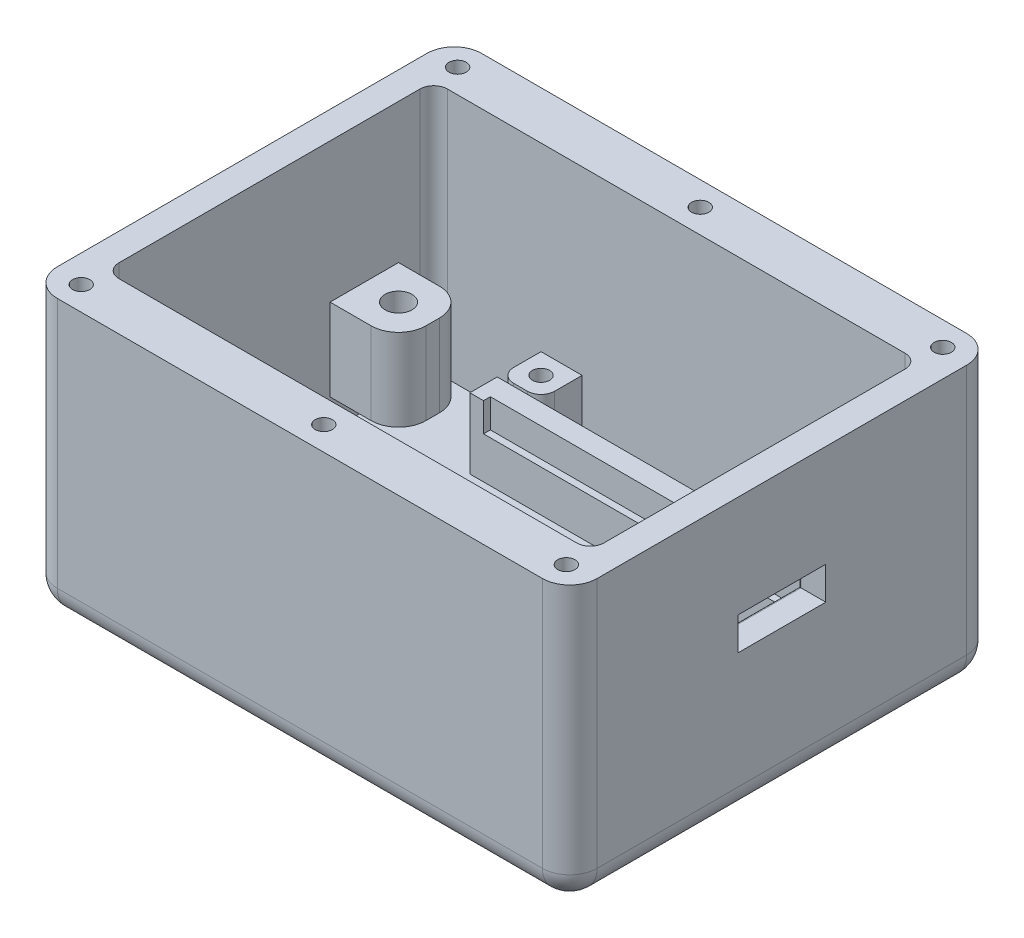
SolidWorks part; units mm, degrees
ref_plane "Front Plane" through (0, 0, 0) normal (0, 0, 1) x (1, 0, 0)
ref_plane "Top Plane" through (0, 0, 0) normal (0, 1, 0) x (1, 0, 0)
ref_plane "Right Plane" through (0, 0, 0) normal (1, 0, 0) x (0, 0, -1)
sketch "Sketch1" plane through (0, 0, 0) normal (0, 1, 0) x (1, 0, 0)
  line L1 (-38.0142, 8.7924) -> (6.9946, 8.7924)
  line L2 (-38.0142, 8.7924) -> (-38.0142, -21.6876)
  line L3 (-38.0142, -21.6876) -> (6.9946, -21.6876)
  line L4 (6.9946, 8.7924) -> (6.9946, -21.6876)
  line L5 (-40.5542, 13.2374) -> (9.5346, 13.2374)
  line L6 (-40.5542, 13.2374) -> (-40.5542, -26.1326)
  line L7 (-40.5542, -26.1326) -> (9.5346, -26.1326)
  line L8 (9.5346, 13.2374) -> (9.5346, -26.1326)
  dimension "D1" = 30.48
  dimension "D2" = 45.0088
  dimension "D3" = 4.445
  dimension "D4" = 4.445
  dimension "D5" = 2.54
  dimension "D6" = 2.54
extrude "Boss-Extrude1" add sketch "Sketch1" along normal blind 23.2918
sketch "Sketch2" plane through (0, 0, 0) normal (0, -1, 0) x (1, 0, 0)
  line L1 (-40.5542, 26.1326) -> (9.5346, 26.1326)
  line L2 (-40.5542, 26.1326) -> (-40.5542, -13.2374)
  line L3 (-40.5542, -13.2374) -> (9.5346, -13.2374)
  line L4 (9.5346, 26.1326) -> (9.5346, -13.2374)
extrude "Boss-Extrude2" add sketch "Sketch2" along normal blind 2.54
sketch "Sketch3" plane through (0, 0, 0) normal (0, 1, 0) x (1, 0, 0)
  line L1 (-28.0574, 4.7284) -> (4.4546, 4.7284)
  line L2 (-28.0574, 4.7284) -> (-28.0574, 2.1884)
  line L3 (-28.0574, 2.1884) -> (4.4546, 2.1884)
  line L4 (4.4546, 4.7284) -> (4.4546, 2.1884)
  line L5 (-28.0574, -15.0836) -> (4.4546, -15.0836)
  line L6 (-28.0574, -15.0836) -> (-28.0574, -17.6236)
  line L7 (-28.0574, -17.6236) -> (4.4546, -17.6236)
  line L8 (4.4546, -15.0836) -> (4.4546, -17.6236)
  line L10 (-38.0142, -21.6876) -> (6.9946, -21.6876) construction
  line L11 (6.9946, -21.6876) -> (6.9946, 8.7924) construction
  dimension "D1" = 2.54
  dimension "D2" = 2.54
  dimension "D3" = 17.272
  dimension "D4" = 4.064
  dimension "D5" = 32.512
  dimension "D6" = 32.512
  dimension "D7" = 2.54
  dimension "D8" = 2.54
extrude "Boss-Extrude3" add sketch "Sketch3" along normal blind 6.5278
hole_wizard "Ø1.6 (1.6) Diameter Hole1" positions "Sketch8" profile "Sketch7" hole size "Ø1.6" standard "ANSI Metric"
sketch "Sketch8" plane through (0, 23.2918, 0) normal (0, 1, 0) x (1, 0, 0)
  line L2 (-40.5542, -26.1326) -> (9.5346, -26.1326) construction
  line L3 (9.5346, 13.2374) -> (-40.5542, 13.2374) construction
  line L4 (-40.5542, 13.2374) -> (-40.5542, -26.1326) construction
  line L5 (9.5346, -26.1326) -> (9.5346, 13.2374) construction
  point P0 (-38.0142, -23.9101)
  point P2 (6.9946, -23.9101)
  point P4 (6.9946, 11.0149)
  point P6 (-38.0142, 11.0149)
  point P8 (-15.5098, 11.0149)
  point P10 (-15.5098, -23.9101)
  point P23 (-15.5098, -26.1326)
  point P24 (-15.5098, 13.2374)
  dimension "D2" = 2.54
  dimension "D3" = 2.54
  dimension "D4" = 2.54
  dimension "D5" = 2.2225
  dimension "D6" = 2.2225
  dimension "D7" = 2.2225
  dimension "D8" = 2.2225
  dimension "D9" = 0
  dimension "D10" = 0
  dimension "D11" = 2.54
  dimension "D12" = 2.2225
  dimension "D13" = 2.2225
sketch "Sketch7" plane through (-38.0142, 23.2918, 23.9101) normal (1, 0, 0) x (0, 0, 1)
  line L0 (0, 0) -> (0, 5.08)
  line L1 (0, 5.08) -> (0.8, 5.08)
  line L2 (0.8, 5.08) -> (0.8, 0)
  line L5 (0.8, 0) -> (0, 0)
  line L10 (0, 5.08) -> (-0.8, 5.08) construction
  line L11 (0, -6.35) -> (0, 107.95) construction
  dimension "Hole Dia." = 1.6
  dimension "Hole Depth" = 5.08
  dimension "Drill Angle" = 180
fillet "Fillet1" radius 2.54 8 edges at (9.5346, -2.54, 6.4476) (-15.5098, -2.54, -13.2374) (-40.5542, -2.54, 6.4476) (-15.5098, -2.54, 26.1326) (9.5346, 10.3759, 26.1326) (-40.5542, 10.3759, 26.1326) (-40.5542, 10.3759, -13.2374) (9.5346, 10.3759, -13.2374)
sketch "Sketch12" plane through (-38.0142, 0, 0) normal (1, 0, 0) x (0, 0, -1)
  line L0 (-21.6876, 23.2918) -> (-21.6876, 0) construction
  line L1 (-18.4237, 10.3378) -> (-12.0737, 10.3378)
  line L2 (-18.4237, 10.3378) -> (-18.4237, 2.7178)
  line L3 (-18.4237, 2.7178) -> (-12.0737, 2.7178)
  line L4 (-12.0737, 10.3378) -> (-12.0737, 2.7178)
  line L5 (-0.8215, 10.3378) -> (5.5285, 10.3378)
  line L6 (-0.8215, 10.3378) -> (-0.8215, 2.7178)
  line L7 (-0.8215, 2.7178) -> (5.5285, 2.7178)
  line L8 (5.5285, 10.3378) -> (5.5285, 2.7178)
  line L9 (8.7924, 0) -> (-21.6876, 0) construction
  line L10 (8.7924, 23.2918) -> (8.7924, 0) construction
  dimension "D1" = 6.35
  dimension "D2" = 6.35
  dimension "D3" = 7.62
  dimension "D4" = 7.62
  dimension "D5" = 3.2639
  dimension "D6" = 3.2639
  dimension "D7" = 2.7178
  dimension "D8" = 2.7178
extrude "Boss-Extrude5" add sketch "Sketch12" along normal blind 6.35
hole_wizard "Ø2.5 (2.5) Diameter Hole2" positions "Sketch14" profile "Sketch13" hole size "Ø2.5" standard "ANSI Metric"
sketch "Sketch14" plane through (0, 10.3378, 0) normal (0, 1, 0) x (1, 0, 0)
  line L0 (-31.6642, -12.0737) -> (-38.0142, -12.0737) construction
  line L1 (-31.6642, -12.0737) -> (-31.6642, -18.4237) construction
  point P0 (-34.8392, -15.2487)
  point P2 (-34.8392, 2.3535)
  dimension "D1" = 17.6022
  dimension "D2" = 3.175
  dimension "D3" = 3.175
sketch "Sketch13" plane through (-34.8392, 10.3378, 15.2487) normal (1, 0, 0) x (0, 0, 1)
  line L0 (0, 0) -> (0, 7.62)
  line L1 (0, 7.62) -> (1.25, 7.62)
  line L2 (1.25, 7.62) -> (1.25, 0)
  line L5 (1.25, 0) -> (0, 0)
  line L11 (0, -6.35) -> (0, 107.95) construction
  dimension "Thru Hole Dia." = 2.5
  dimension "Thru Hole Depth" = 7.62
fillet "Fillet2" radius 2.54 4 edges at (-31.6642, 6.5278, -5.5285) (-31.6642, 6.5278, 0.8215) (-31.6642, 6.5278, 12.0737) (-31.6642, 6.5278, 18.4237)
sketch "Sketch15" plane through (0, 0, 0) normal (0, 1, 0) x (1, 0, 0)
  line L0 (6.9946, 8.7924) -> (-38.0142, 8.7924) construction
  line L1 (6.9946, 8.7924) -> (3.1846, 8.7924)
  line L2 (6.9946, 8.7924) -> (6.9946, 4.9824)
  line L3 (6.9946, 4.9824) -> (3.1846, 4.9824)
  line L4 (3.1846, 8.7924) -> (3.1846, 4.9824)
  line L5 (-28.0574, 8.7924) -> (-24.2474, 8.7924)
  line L6 (-28.0574, 8.7924) -> (-28.0574, 4.9824)
  line L7 (-28.0574, 4.9824) -> (-24.2474, 4.9824)
  line L8 (-24.2474, 8.7924) -> (-24.2474, 4.9824)
  line L9 (-38.0142, -21.6876) -> (6.9946, -21.6876) construction
  line L10 (-28.0574, -21.6876) -> (-24.2474, -21.6876)
  line L11 (-28.0574, -21.6876) -> (-28.0574, -17.8776)
  line L12 (-28.0574, -17.8776) -> (-24.2474, -17.8776)
  line L13 (-24.2474, -21.6876) -> (-24.2474, -17.8776)
  line L15 (6.9946, -21.6876) -> (3.1846, -21.6876)
  line L16 (6.9946, -21.6876) -> (6.9946, -17.8776)
  line L17 (6.9946, -17.8776) -> (3.1846, -17.8776)
  line L18 (3.1846, -21.6876) -> (3.1846, -17.8776)
  dimension "D1" = 3.81
  dimension "D2" = 3.81
  dimension "D3" = 3.81
  dimension "D4" = 3.81
  dimension "D5" = 3.81
  dimension "D6" = 3.81
  dimension "D7" = 3.81
  dimension "D8" = 3.81
  dimension "D9" = 35.052
  dimension "D10" = 35.052
sketch "Sketch17" plane through (4.4546, 0, 0) normal (1, 0, 0) x (0, 0, -1)
  line L1 (2.1884, 6.5278) -> (2.8234, 6.5278)
  line L2 (2.1884, 6.5278) -> (2.1884, 3.8608)
  line L3 (2.1884, 3.8608) -> (2.8234, 3.8608)
  line L4 (2.8234, 6.5278) -> (2.8234, 3.8608)
  dimension "D1" = 2.667
  dimension "D2" = 0.635
extrude "Cut-Extrude3" cut sketch "Sketch17" against normal blind 31.242
sketch "Sketch18" plane through (4.4546, 0, 0) normal (1, 0, 0) x (0, 0, -1)
  line L1 (-15.0836, 6.5278) -> (-15.7186, 6.5278)
  line L2 (-15.0836, 6.5278) -> (-15.0836, 3.8608)
  line L3 (-15.0836, 3.8608) -> (-15.7186, 3.8608)
  line L4 (-15.7186, 6.5278) -> (-15.7186, 3.8608)
  dimension "D1" = 2.667
  dimension "D2" = 0.635
extrude "Cut-Extrude5" cut sketch "Sketch18" against normal blind 31.242
extrude "Boss-Extrude6" add sketch "Sketch15" along normal blind 6.5278
fillet "Fillet3" radius 1.27 6 edges at (3.1846, 3.2639, -4.9824) (3.1846, 3.2639, 17.8776) (-24.2474, 3.2639, -4.9824) (-28.0574, 3.2639, -4.9824) (-24.2474, 3.2639, 17.8776) (-28.0574, 3.2639, 17.8776)
hole_wizard "Ø1.6 (1.6) Diameter Hole2" positions "Sketch22" profile "Sketch21" hole size "Ø1.6" standard "ANSI Metric"
sketch "Sketch22" plane through (0, 6.5278, 0) normal (0, 1, 0) x (1, 0, 0)
  line L2 (-28.0574, -21.6876) -> (-24.2474, -21.6876) construction
  line L3 (-24.2474, -21.6876) -> (-24.2474, -19.1476) construction
  line L4 (-28.0574, 8.7924) -> (-28.0574, 6.2524) construction
  line L5 (-26.7874, 4.9824) -> (-25.5174, 4.9824) construction
  line L6 (3.1846, 8.7924) -> (3.1846, 6.2524) construction
  line L7 (4.4546, 4.9824) -> (6.9946, 4.9824) construction
  line L8 (3.1846, -19.1476) -> (3.1846, -21.6876) construction
  line L9 (3.1846, -21.6876) -> (6.9946, -21.6876) construction
  point P0 (-26.1524, -19.7826)
  point P2 (-26.1524, 6.8874)
  point P4 (5.0896, 6.8874)
  point P6 (5.0896, -19.7826)
  dimension "D1" = 1.905
  dimension "D2" = 1.905
  dimension "D3" = 1.905
  dimension "D4" = 1.905
  dimension "D5" = 1.905
  dimension "D6" = 1.905
  dimension "D7" = 1.905
  dimension "D8" = 1.905
sketch "Sketch21" plane through (-26.1524, 6.5278, 19.7826) normal (1, 0, 0) x (0, 0, 1)
  line L0 (0, 0) -> (0, 5.08)
  line L1 (0, 5.08) -> (0.8, 5.08)
  line L2 (0.8, 5.08) -> (0.8, 0)
  line L5 (0.8, 0) -> (0, 0)
  line L10 (0, 5.08) -> (-0.8, 5.08) construction
  line L11 (0, -6.35) -> (0, 107.95) construction
  dimension "Hole Dia." = 1.6
  dimension "Hole Depth" = 5.08
  dimension "Drill Angle" = 180
sketch "Sketch23" plane through (9.5346, 0, 0) normal (1, 0, 0) x (0, 0, -1)
  line L1 (-10.5116, 13.8303) -> (-2.3836, 13.8303)
  line L2 (-10.5116, 13.8303) -> (-10.5116, 10.7823)
  line L3 (-10.5116, 10.7823) -> (-2.3836, 10.7823)
  line L4 (-2.3836, 13.8303) -> (-2.3836, 10.7823)
  line L5 (-23.5926, 23.2918) -> (-23.5926, 0) construction
  line L7 (-23.5926, 0) -> (10.6974, 0) construction
  dimension "D1" = 8.128
  dimension "D2" = 3.048
  dimension "D3" = 13.081
  dimension "D4" = 10.7823
extrude "Cut-Extrude6" cut sketch "Sketch23" against normal up to next
fillet "Fillet4" radius 0.254 4 edges at (6.9946, 12.3063, 10.5116) (6.9946, 13.8303, 6.4476) (6.9946, 10.7823, 6.4476) (6.9946, 12.3063, 2.3836)
fillet "Fillet5" radius 1.27 4 edges at (-38.0142, 11.6459, -8.7924) (6.9946, 14.9098, -8.7924) (6.9946, 14.9098, 21.6876) (-38.0142, 11.6459, 21.6876)
